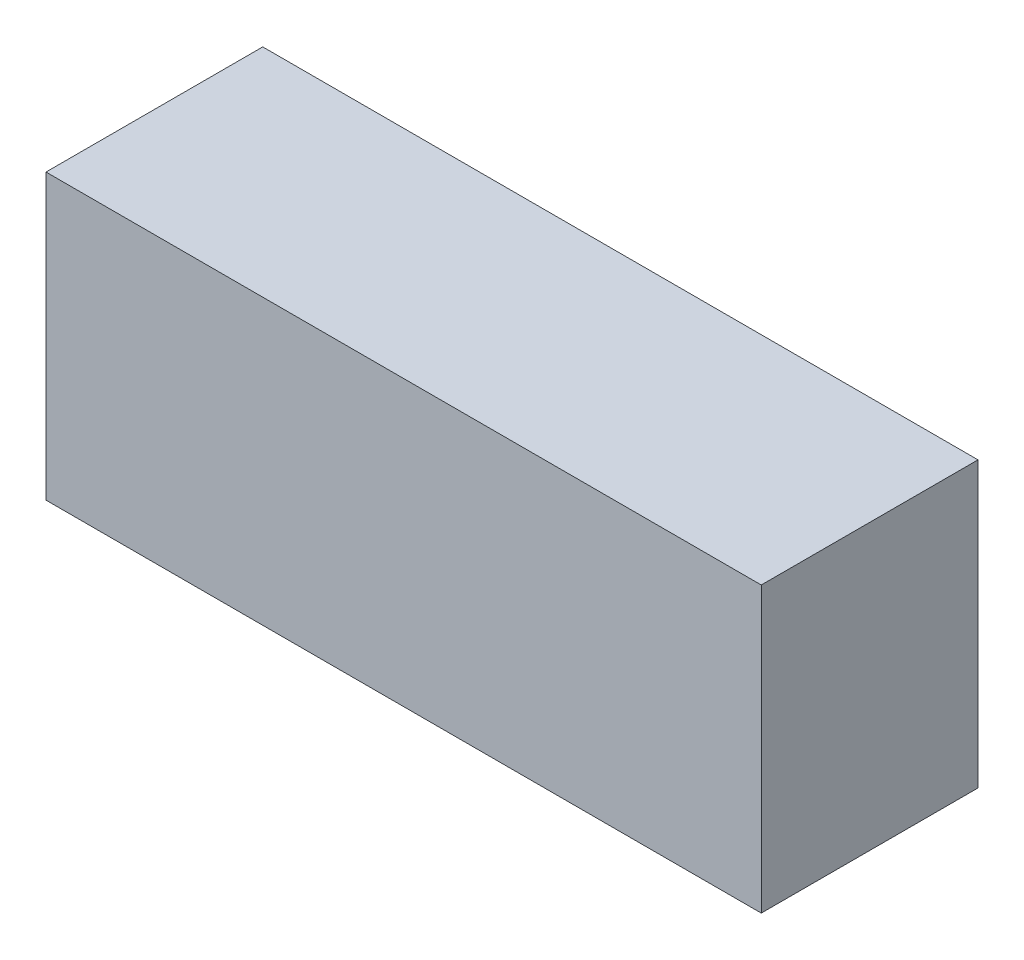
SolidWorks part; units mm, degrees
ref_plane "Alzado" through (0, 0, 0) normal (0, 0, 1) x (1, 0, 0)
ref_plane "Planta" through (0, 0, 0) normal (0, 1, 0) x (1, 0, 0)
ref_plane "Vista lateral" through (0, 0, 0) normal (1, 0, 0) x (0, 0, -1)
sketch "Croquis1" plane through (0, 0, 0) normal (0, 0, 1) x (1, 0, 0)
  line L1 (-44.55, -17.7) -> (44.55, -17.7)
  line L2 (-44.55, -17.7) -> (-44.55, 17.7)
  line L3 (-44.55, 17.7) -> (44.55, 17.7)
  line L4 (44.55, -17.7) -> (44.55, 17.7)
  line L5 (-44.55, -17.7) -> (44.55, 17.7) construction
  line L6 (-44.55, 17.7) -> (44.55, -17.7) construction
  point P0 (0, 0)
  dimension "D1" = 89.1
  dimension "D2" = 35.4
extrude "Saliente-Extruir1" add sketch "Croquis1" along normal blind 27
